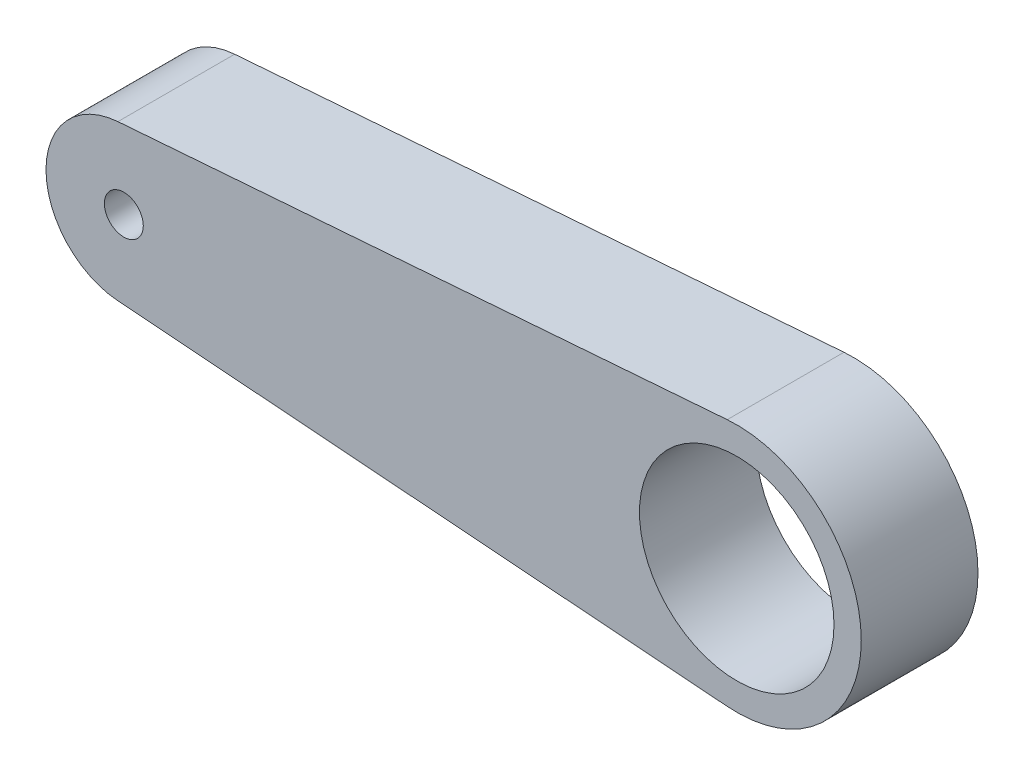
SolidWorks part; units mm, degrees
ref_plane "Alzado" through (0, 0, 0) normal (0, 0, 1) x (1, 0, 0)
ref_plane "Planta" through (0, 0, 0) normal (0, 1, 0) x (1, 0, 0)
ref_plane "Vista lateral" through (0, 0, 0) normal (1, 0, 0) x (0, 0, -1)
sketch "Croquis2" plane through (0, 0, 0) normal (0, 0, 1) x (1, 0, 0)
  line L0 (0, 0) -> (18.95, 0) construction
  line L1 (-0.1524, 1.9942) -> (15.5062, 3.1907)
  line L4 (-0.1524, -1.9942) -> (15.5062, -3.1907)
  circle A0 centre (0, 0) radius 2
  circle A3 centre (0, 0) radius 0.5
  circle A4 centre (15.75, 0) radius 2.5
  circle A5 centre (15.75, 0) radius 3.2
  dimension "D1" = 1
  dimension "D2" = 4
  dimension "D3" = 15.75
  dimension "D4" = 6.4
  dimension "D6" = 5
extrude "Saliente-Extruir1" add sketch "Croquis2" along normal mid plane 3
